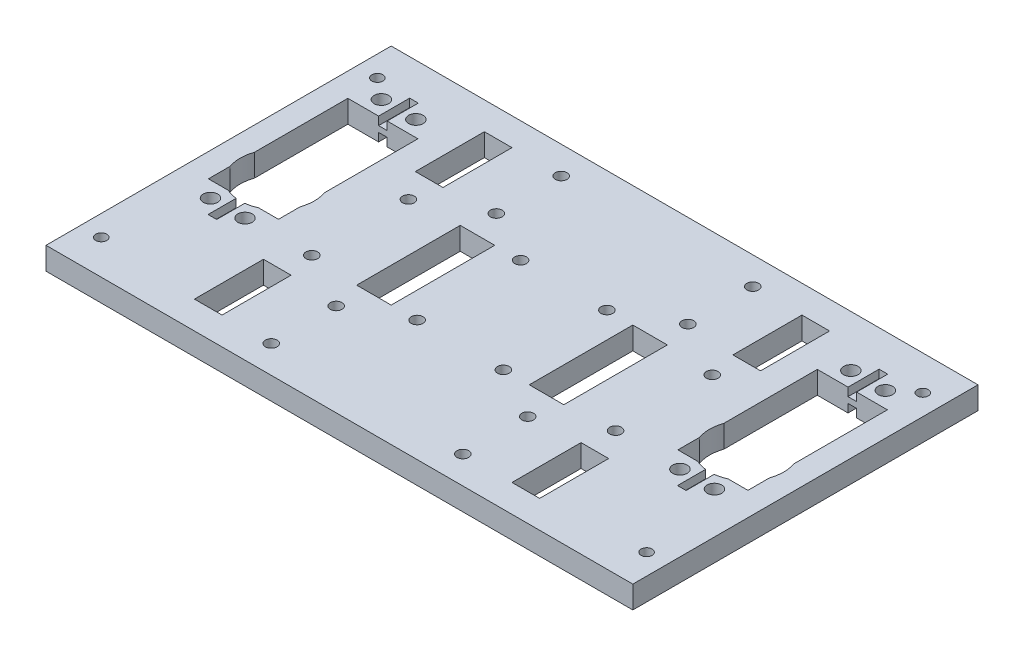
SolidWorks part; units mm, degrees
ref_plane "前视基准面" through (0, 0, 0) normal (0, 0, 1) x (1, 0, 0)
ref_plane "上视基准面" through (0, 0, 0) normal (0, 1, 0) x (1, 0, 0)
ref_plane "右视基准面" through (0, 0, 0) normal (1, 0, 0) x (0, 0, -1)
sketch "草图1" plane through (0, 0, 0) normal (0, 1, 0) x (1, 0, 0)
  line L1 (-50, -50) -> (50, -50)
  line L2 (-50, -50) -> (-50, 50)
  line L3 (-50, 50) -> (50, 50)
  line L4 (50, -50) -> (50, 50)
  line L5 (-50, -50) -> (50, 50) construction
  line L6 (-50, 50) -> (50, -50) construction
  point P0 (0, 0)
  dimension "D1" = 100
  dimension "D2" = 100
extrude "凸台-拉伸1" add sketch "草图1" along normal blind 6.5
sketch "草图2" plane through (0, 0, 0) normal (0, -1, 0) x (1, 0, 0)
  line L5 (0, -5.3625) -> (0, 5.3625) construction
  line L6 (-37, -50) -> (-32, -50)
  line L7 (-37, -50) -> (-37, 50)
  line L8 (-37, 50) -> (-32, 50)
  line L13 (-32, -50) -> (-32, 50)
  line L14 (-37, -50) -> (-32, 50) construction
  line L15 (-37, 50) -> (-32, -50) construction
  line L16 (37, 50) -> (32, -50) construction
  line L17 (37, -50) -> (32, 50) construction
  line L18 (32, -50) -> (32, 50)
  line L19 (37, 50) -> (32, 50)
  line L20 (37, -50) -> (37, 50)
  line L21 (37, -50) -> (32, -50)
  point P0 (-34.5, 0)
  point P11 (34.5, 0)
  dimension "D1" = 5
  dimension "D2" = 64
  dimension "D3" = 100
extrude "凸台-拉伸2" add sketch "草图2" along normal blind 75
sketch "草图3" plane through (-37, 0, 0) normal (-1, 0, 0) x (0, 0, 1)
  line L0 (0, -5.3625) -> (0, 5.3625) construction
  line L1 (50, 0) -> (-50, 0) construction
  line L2 (4.925, -12) -> (4.925, -61.42) construction
  line L3 (4.925, -36.71) -> (59.1857, -36.71) construction
  circle A0 centre (-4.925, -12) radius 2.25
  circle A1 centre (4.925, -12) radius 2.25
  circle A3 centre (-4.925, -61.42) radius 2.25
  circle A4 centre (4.925, -61.42) radius 2.25
  circle A5 centre (14.7735, -12.1723) radius 2.25
  circle A6 centre (14.7735, -61.2477) radius 2.25
  circle A7 centre (-14.7735, -61.2477) radius 2.25
  circle A8 centre (-14.7735, -12.1723) radius 2.25
  dimension "D1" = 9.85
  dimension "D2" = 12
  dimension "D3" = 2
  dimension "D4" = 9.85
  dimension "D5" = 4.5
  dimension "D6" = 4.5
extrude "切除-拉伸1" cut sketch "草图3" against normal blind 85
sketch "草图4" plane through (-37, 0, 0) normal (-1, 0, 0) x (0, 0, 1)
  line L2 (-20, -57.42) -> (20, -57.42)
  line L3 (-20, -57.42) -> (-20, -16)
  line L4 (-20, -16) -> (20, -16)
  line L5 (20, -57.42) -> (20, -16)
  line L6 (-20, -57.42) -> (20, -16) construction
  line L7 (-20, -16) -> (20, -57.42) construction
  circle A3 centre (-4.925, -12) radius 2.25 construction
  circle A4 centre (-4.925, -61.42) radius 2.25 construction
  point P4 (0, -36.71)
  dimension "D2" = 4
  dimension "D1" = 4
  dimension "D3" = 40
extrude "切除-拉伸2" cut sketch "草图4" against normal blind 85
chamfer "倒角1" distance 10 angle 45 4 edges at (34.5, -75, 50) (-34.5, -75, 50) (34.5, -75, -50) (-34.5, -75, -50)
sketch "草图5" plane through (0, 6.5, 0) normal (0, 1, 0) x (1, 0, 0)
  line L0 (0, -5.3625) -> (0, 5.3625) construction
  line L1 (-30, -15) -> (-20, -15)
  line L2 (-30, -15) -> (-30, 15)
  line L3 (-30, 15) -> (-20, 15)
  line L4 (-20, -15) -> (-20, 15)
  line L5 (-30, -15) -> (-20, 15) construction
  line L6 (-30, 15) -> (-20, -15) construction
  line L7 (30, 15) -> (20, -15) construction
  line L8 (30, -15) -> (20, 15) construction
  line L9 (20, -15) -> (20, 15)
  line L10 (30, 15) -> (20, 15)
  line L11 (30, -15) -> (30, 15)
  line L12 (30, -15) -> (20, -15)
  point P0 (-25, 0)
  point P11 (25, 0)
  dimension "D1" = 10
  dimension "D2" = 40
  dimension "D3" = 30
extrude "切除-拉伸3" cut sketch "草图5" against normal blind 85
ref_plane "基准面4" through (0, 26.5, 0) normal (0, 1, 0) x (1, 0, 0)
sketch "草图11" plane through (0, 0, 0) normal (0, -1, 0) x (1, 0, 0)
  line L0 (-50, -50) -> (-50, 50) construction
  line L1 (-50, 50) -> (-37, 50) construction
  line L2 (0, -5.3625) -> (0, 5.3625) construction
  line L3 (5.3625, 0) -> (-5.3625, 0) construction
  circle A0 centre (-44, 38) radius 1.7
  circle A1 centre (-44, 26) radius 1.7
  circle A2 centre (-44, 14) radius 1.7
  circle A3 centre (44, 14) radius 1.7
  circle A4 centre (44, 26) radius 1.7
  circle A5 centre (44, 38) radius 1.7
  circle A6 centre (44, -38) radius 1.7
  circle A7 centre (44, -26) radius 1.7
  circle A8 centre (44, -14) radius 1.7
  circle A9 centre (-44, -14) radius 1.7
  circle A10 centre (-44, -26) radius 1.7
  circle A11 centre (-44, -38) radius 1.7
  dimension "D1" = 3.4
  dimension "D2" = 6
  dimension "D3" = 12
  dimension "D4" = 3
extrude "切除-拉伸5" cut sketch "草图11" against normal blind 10
sketch "草图12" plane through (0, 6.5, 0) normal (0, 1, 0) x (1, 0, 0)
  line L1 (0, -5.3625) -> (0, 5.3625) construction
  line L2 (50, 50) -> (-50, 50) construction
  line L3 (-5.3625, 0) -> (5.3625, 0) construction
  circle A0 centre (-27.75, 42) radius 1.7
  circle A2 centre (-27.75, 23.2) radius 1.7
  circle A3 centre (27.75, 23.2) radius 1.7
  circle A4 centre (27.75, 42) radius 1.7
  circle A5 centre (27.75, -42) radius 1.7
  circle A6 centre (27.75, -23.2) radius 1.7
  circle A7 centre (-27.75, -23.2) radius 1.7
  circle A8 centre (-27.75, -42) radius 1.7
  dimension "D1" = 18.8
  dimension "D2" = 3.4
  dimension "D3" = 3.4
  dimension "D4" = 55.5
  dimension "D5" = 8
extrude "切除-拉伸6" cut sketch "草图12" against normal blind 25
sketch "草图13" plane through (-37, 0, 0) normal (-1, 0, 0) x (0, 0, 1)
  line L0 (50, -65) -> (50, 0) construction
  line L1 (50, 0) -> (-50, 0) construction
  line L3 (46, -16) -> (46, -51) construction
  circle A0 centre (46, -16) radius 2.3
  circle A1 centre (46, -51) radius 2.3
  circle A4 centre (46, -33.5) radius 15
  dimension "D1" = 35
  dimension "D2" = 4.6
  dimension "D3" = 4.6
  dimension "D4" = 4
  dimension "D5" = 16
  dimension "D6" = 30
extrude "切除-拉伸9" cut sketch "草图13" against normal blind 105
sketch "草图14" plane through (-37, 0, 0) normal (-1, 0, 0) x (0, 0, 1)
  line L0 (-20, -57.42) -> (20, -57.42) construction
  line L1 (-20, -16) -> (-35, -16)
  line L2 (-20, -16) -> (-20, -57.42)
  line L3 (-20, -57.42) -> (-35, -57.42)
  line L4 (-35, -16) -> (-35, -57.42)
  dimension "D1" = 15
extrude "切除-拉伸10" cut sketch "草图14" against normal blind 83
sketch "草图15" plane through (-37, 0, 0) normal (-1, 0, 0) x (0, 0, 1)
  line L0 (-35, -16) -> (-35, -57.42) construction
  line L1 (-15.5119, -57.42) -> (-54.4881, -57.42)
  line L2 (-15.5119, -57.42) -> (-15.5119, -16)
  line L3 (-15.5119, -16) -> (-54.4881, -16)
  line L4 (-54.4881, -57.42) -> (-54.4881, -16)
  line L5 (-15.5119, -57.42) -> (-54.4881, -16) construction
  line L6 (-15.5119, -16) -> (-54.4881, -57.42) construction
  line L7 (-35, -57.42) -> (20, -57.42) construction
  point P0 (-35, -36.71)
extrude "切除-拉伸11" cut sketch "草图15" against normal blind 83
sketch "草图16" plane through (0, 6.5, 0) normal (0, 1, 0) x (1, 0, 0)
  line L0 (0, -5.3625) -> (0, 5.3625) construction
  line L1 (-5.3625, 0) -> (5.3625, 0) construction
  circle A0 centre (-12.5, 15) radius 1.7
  circle A1 centre (12.5, 15) radius 1.7
  circle A2 centre (12.5, -15) radius 1.7
  circle A3 centre (-12.5, -15) radius 1.7
  dimension "D1" = 3.4
  dimension "D2" = 25
  dimension "D3" = 30
extrude "切除-拉伸12" cut sketch "草图16" against normal blind 83
sketch "草图17" plane through (-37, 0, 0) normal (-1, 0, 0) x (0, 0, 1)
  line L0 (20, -36.71) -> (2.0906, -36.71) construction
  line L2 (20, -57.42) -> (20, -16) construction
  circle A0 centre (-24.6235, -12.1723) radius 2.15
  circle A1 centre (-14.7735, -12.1723) radius 2.25 construction
  circle A2 centre (-24.625, -61.42) radius 2.15
  circle A3 centre (-39.6225, -11.9996) radius 2.15
  circle A4 centre (-39.6225, -61.4204) radius 2.15
  point P4 (-14.7735, -12.1723)
  dimension "D1" = 9.85
  dimension "D2" = 4.3
  dimension "D3" = 4.3
  dimension "D4" = 15
extrude "切除-拉伸13" cut sketch "草图17" against normal blind 83
chamfer "倒角2" distance 8 angle 45 2 edges at (34.5, -16, -50) (-34.5, -16, -50)
sketch "草图18" plane through (0, 0, 0) normal (1, 0, 0) x (0, 0, -1)
  line L1 (-50, 0) -> (93.5683, 0)
  line L2 (-50, 0) -> (-50, -92.866)
  line L3 (-50, -92.866) -> (93.5683, -92.866)
  line L4 (93.5683, 0) -> (93.5683, -92.866)
extrude "切除-拉伸14" cut sketch "草图18" against normal mid plane 110
sketch "草图19" plane through (0, 0, 0) normal (0, 1, 0) x (1, 0, 0)
  line L0 (0, -5.3625) -> (0, 5.3625) construction
  line L1 (-50, -50) -> (-85, -50)
  line L2 (-50, -50) -> (-50, 50)
  line L3 (-50, 50) -> (-85, 50)
  line L4 (-85, -50) -> (-85, 50)
  line L5 (85, -50) -> (85, 50)
  line L6 (50, 50) -> (85, 50)
  line L7 (50, -50) -> (50, 50)
  line L8 (50, -50) -> (85, -50)
  dimension "D1" = 35
extrude "凸台-拉伸3" add sketch "草图19" along normal blind 6.5
sketch "草图21" plane through (0, 0, 0) normal (0, -1, 0) x (1, 0, 0)
  line L0 (0, -25.4568) -> (0, 25.4568) construction
  line L1 (-85, -50) -> (-85, 50) construction
  circle A0 centre (-68, 0) radius 10.75
  circle A1 centre (68, 0) radius 10.75
  dimension "D1" = 17
extrude "切除-拉伸16" cut sketch "草图21" against normal blind 10
sketch "草图20" plane through (0, 6.5, 0) normal (0, 1, 0) x (1, 0, 0)
  line L0 (0, -5.3625) -> (0, 5.3625) construction
  line L1 (-85, 50) -> (-85, -50) construction
  circle A2 centre (-63, -14.35) radius 2.1
  circle A3 centre (-73, -14.35) radius 2.1
  circle A8 centre (-73, 35.15) radius 2.1
  circle A9 centre (-68, 0) radius 10.75 construction
  circle A10 centre (-63, 35.15) radius 2.1
  circle A11 centre (63, 35.15) radius 2.1
  circle A12 centre (73, 35.15) radius 2.1
  circle A13 centre (73, -14.35) radius 2.1
  circle A14 centre (63, -14.35) radius 2.1
  dimension "D1" = 4.2
  dimension "D2" = 4.2
  dimension "D3" = 2
  dimension "D4" = 14.35
  dimension "D5" = 12
  dimension "D6" = 10
extrude "切除-拉伸15" cut sketch "草图20" against normal mid plane 15
sketch "草图23" plane through (0, 6.5, 0) normal (0, 1, 0) x (1, 0, 0)
  line L0 (-73, -14.35) -> (-63, -14.35) construction
  line L1 (-73, -14.35) -> (-73, 35.15) construction
  line L2 (-73, 10.4) -> (-63.3177, 10.4) construction
  line L3 (-68, -14.35) -> (-68, 10.4) construction
  line L4 (0, -5.3625) -> (0, 5.3625) construction
  line L5 (-78.15, 30.6) -> (-57.85, 30.6)
  line L6 (-78.15, 30.6) -> (-78.15, -9.8)
  line L7 (-78.15, -9.8) -> (-57.85, -9.8)
  line L8 (-57.85, 30.6) -> (-57.85, -9.8)
  line L9 (-78.15, 30.6) -> (-57.85, -9.8) construction
  line L10 (-78.15, -9.8) -> (-57.85, 30.6) construction
  line L11 (78.15, -9.8) -> (57.85, 30.6) construction
  line L12 (78.15, 30.6) -> (57.85, -9.8) construction
  line L13 (68, -14.35) -> (68, 10.4) construction
  line L14 (73, 10.4) -> (63.3177, 10.4) construction
  line L15 (73, -14.35) -> (73, 35.15) construction
  line L16 (73, -14.35) -> (63, -14.35) construction
  line L17 (57.85, 30.6) -> (57.85, -9.8)
  line L18 (78.15, -9.8) -> (57.85, -9.8)
  line L19 (78.15, 30.6) -> (78.15, -9.8)
  line L20 (78.15, 30.6) -> (57.85, 30.6)
  dimension "D1" = 20.3
  dimension "D2" = 40.4
extrude "切除-拉伸17" cut sketch "草图23" against normal blind 20
sketch "草图24" plane through (0, 6.5, 0) normal (0, 1, 0) x (1, 0, 0)
  line L0 (-57.85, 30.6) -> (-78.15, 30.6) construction
  line L1 (-66.75, 21.6) -> (-69.25, 21.6)
  line L2 (-66.75, 21.6) -> (-66.75, 39.6)
  line L3 (-66.75, 39.6) -> (-69.25, 39.6)
  line L4 (-69.25, 21.6) -> (-69.25, 39.6)
  line L5 (-66.75, 21.6) -> (-69.25, 39.6) construction
  line L6 (-66.75, 39.6) -> (-69.25, 21.6) construction
  line L7 (-78.15, 30.6) -> (-78.15, -9.8) construction
  line L8 (-78.15, 10.4) -> (0, 10.4) construction
  line L9 (0, -5.3625) -> (0, 5.3625) construction
  line L10 (66.75, 39.6) -> (69.25, 21.6) construction
  line L11 (66.75, 21.6) -> (69.25, 39.6) construction
  line L12 (69.25, 21.6) -> (69.25, 39.6)
  line L13 (66.75, 39.6) -> (69.25, 39.6)
  line L14 (66.75, 21.6) -> (66.75, 39.6)
  line L15 (66.75, 21.6) -> (69.25, 21.6)
  line L17 (66.75, -0.8) -> (69.25, -18.8) construction
  line L18 (66.75, -18.8) -> (69.25, -0.8) construction
  line L19 (-66.75, -18.8) -> (-69.25, -0.8) construction
  line L20 (-66.75, -0.8) -> (-69.25, -18.8) construction
  line L21 (66.75, -0.8) -> (69.25, -0.8)
  line L22 (66.75, -0.8) -> (66.75, -18.8)
  line L23 (66.75, -18.8) -> (69.25, -18.8)
  line L24 (69.25, -0.8) -> (69.25, -18.8)
  line L25 (-69.25, -0.8) -> (-69.25, -18.8)
  line L26 (-66.75, -18.8) -> (-69.25, -18.8)
  line L27 (-66.75, -0.8) -> (-66.75, -18.8)
  line L28 (-66.75, -0.8) -> (-69.25, -0.8)
  point P0 (-68, 30.6)
  point P19 (68, 30.6)
  point P30 (68, -9.8)
  point P31 (-68, -9.8)
  dimension "D1" = 2.5
  dimension "D2" = 9
extrude "切除-拉伸18" cut sketch "草图24" against normal blind 2.4
sketch "草图25" plane through (0, 6.5, 0) normal (0, 1, 0) x (1, 0, 0)
  line L0 (85, 50) -> (-85, 50) construction
  line L1 (-85, 50) -> (-85, -50) construction
  line L2 (0, -3.575) -> (0, 3.575) construction
  line L3 (-3.575, 0) -> (3.575, 0) construction
  circle A0 centre (-79, 40) radius 1.6
  circle A1 centre (-87.3205, 27.5192) radius 1.6
  circle A2 centre (87.3205, 27.5192) radius 1.6
  circle A3 centre (79, 40) radius 1.6
  circle A4 centre (79, -40) radius 1.6
  circle A5 centre (87.3205, -27.5192) radius 1.6
  circle A6 centre (-87.3205, -27.5192) radius 1.6
  circle A7 centre (-79, -40) radius 1.6
  dimension "D1" = 15
  dimension "D2" = 10
  dimension "D3" = 6
  dimension "D4" = 3.2
  dimension "D5" = 3.2
extrude "切除-拉伸19" cut sketch "草图25" against normal blind 10
sketch "草图26" plane through (0, 6.5, 0) normal (0, 1, 0) x (1, 0, 0)
  line L0 (-85, -50) -> (85, -50) construction
  line L1 (-42, -42) -> (-50, -42)
  line L2 (-42, -42) -> (-42, -22)
  line L3 (-42, -22) -> (-50, -22)
  line L4 (-50, -42) -> (-50, -22)
  line L5 (-85, 50) -> (-85, -50) construction
  line L6 (0, -3.575) -> (0, 3.575) construction
  line L7 (50, -42) -> (50, -22)
  line L8 (42, -22) -> (50, -22)
  line L9 (42, -42) -> (42, -22)
  line L10 (42, -42) -> (50, -42)
  line L11 (-3.575, 0) -> (3.575, 0) construction
  line L12 (42, 42) -> (50, 42)
  line L13 (42, 42) -> (42, 22)
  line L14 (42, 22) -> (50, 22)
  line L15 (50, 42) -> (50, 22)
  line L16 (-50, 42) -> (-50, 22)
  line L17 (-42, 22) -> (-50, 22)
  line L18 (-42, 42) -> (-42, 22)
  line L19 (-42, 42) -> (-50, 42)
  dimension "D1" = 8
  dimension "D2" = 20
  dimension "D3" = 8
  dimension "D4" = 35
extrude "切除-拉伸20" cut sketch "草图26" against normal blind 23
ref_plane "基准面5" through (0, 3.25, 0) normal (0, 1, 0) x (1, 0, 0)
mirror "镜向1" about plane through (0, 3.25, 0) normal (0, 1, 0) of "切除-拉伸18"
